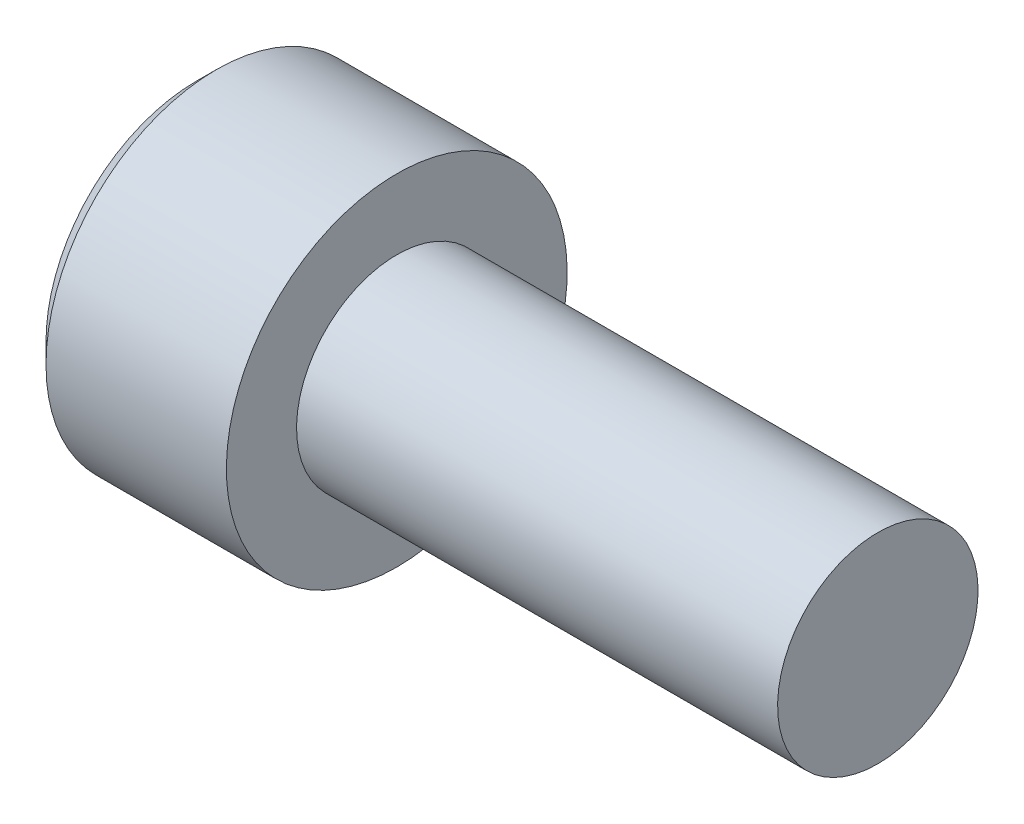
SolidWorks part; units mm, degrees
ref_plane "Front Plane" through (0, 0, 0) normal (0, 0, 1) x (1, 0, 0)
ref_plane "Top Plane" through (0, 0, 0) normal (0, 1, 0) x (1, 0, 0)
ref_plane "Right Plane" through (0, 0, 0) normal (1, 0, 0) x (0, 0, -1)
sketch "Sketch1" plane through (0, 0, 0) normal (0, 0, 1) x (1, 0, 0)
  line L0 (-5, 0) -> (12, 0) construction
  line L1 (-5, 0) -> (-5, 4.25)
  line L2 (-5, 4.25) -> (0, 4.25)
  line L3 (0, 4.25) -> (0, 2.5)
  line L4 (0, 2.5) -> (12, 2.5)
  line L5 (12, 2.5) -> (12, 0)
  line L6 (-5, 0) -> (12, 0)
  dimension "MSM_33" = 5
  dimension "MSM_31" = 12
  dimension "MSM_32" = 5
  dimension "MSM_34" = 8.5
revolve "Revolve1" add sketch "Sketch1" angle 360 about L0
cosmetic thread "Thread1" parameters "ATD_1"=4.134
sketch "Sketch2" plane through (0, 0, 0) normal (0, 0, 1) x (1, 0, 0)
  line L0 (-5, 0) -> (-1.3453, 0) construction
  line L1 (-5, 0) -> (-1.3453, 0)
  line L2 (-2.5, 2) -> (-1.3453, 0)
  line L3 (-2.5, 2) -> (-5, 2)
  line L4 (-5, 2) -> (-5, 0)
  line L5 (-5, 0) -> (-5, 4.25) construction
  dimension "FIX_2" = 60
  dimension "MSM_36" = 4
  dimension "MSM_35" = 2.5
revolve "Cut-Revolve1" cut sketch "Sketch2" angle 360 about L0
sketch "Sketch3" plane through (-5, 0, 0) normal (-1, 0, 0) x (0, 0, 1)
  line L1 (0, 2.3094) -> (-2, 1.1547)
  line L2 (-2, 1.1547) -> (-2, -1.1547)
  line L3 (-2, -1.1547) -> (0, -2.3094)
  line L4 (0, -2.3094) -> (2, -1.1547)
  line L5 (2, -1.1547) -> (2, 1.1547)
  line L6 (2, 1.1547) -> (0, 2.3094)
  circle A0 centre (0, 0) radius 2 construction
  dimension "MSM_36" = 4
extrude "Cut-Extrude1" cut sketch "Sketch3" against normal blind 2.5
chamfer "Chamfer1" distance 0.5 1 edges at (-5, -4.25, 0)
